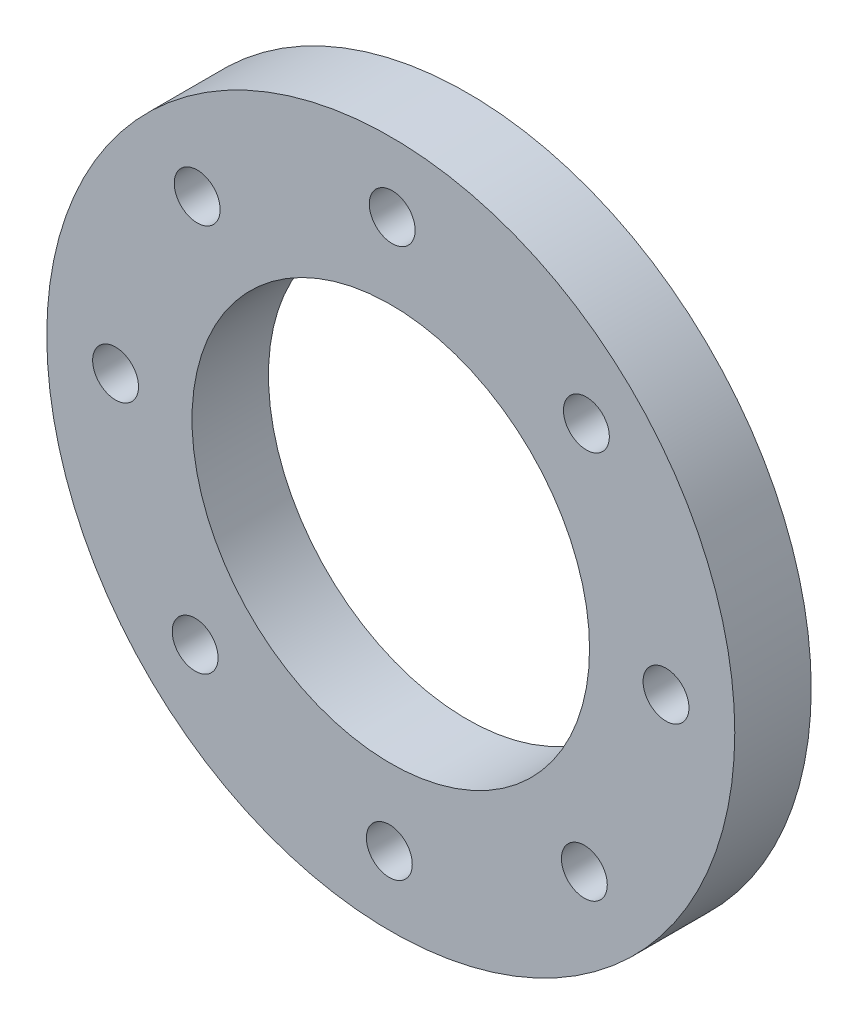
SolidWorks part; units mm, degrees
ref_plane "Plan de face" through (0, 0, 0) normal (0, 0, 1) x (1, 0, 0)
ref_plane "Plan de dessus" through (0, 0, 0) normal (0, 1, 0) x (1, 0, 0)
ref_plane "Plan de droite" through (0, 0, 0) normal (1, 0, 0) x (0, 0, -1)
sketch "Esquisse1" plane through (0, 0, 0) normal (0, 0, 1) x (1, 0, 0)
  circle A0 centre (0, 0) radius 22.5
  circle A1 centre (0, 0) radius 13
  circle A2 centre (-12.6609, 12.7946) radius 1.5
  circle A6 centre (0.0946, 17.9998) radius 1.5
  circle A7 centre (12.7946, 12.6609) radius 1.5
  circle A8 centre (17.9998, -0.0946) radius 1.5
  circle A9 centre (12.6609, -12.7946) radius 1.5
  circle A10 centre (-0.0946, -17.9998) radius 1.5
  circle A11 centre (-12.7946, -12.6609) radius 1.5
  circle A12 centre (-17.9998, 0.0946) radius 1.5
  point P15 (0, 0)
  dimension "D1" = 26
  dimension "D3" = 3
  dimension "D5" = 45
  dimension "D2" = 18
  dimension "D4" = 8
extrude "Boss.-Extru.1" add sketch "Esquisse1" along normal blind 5
